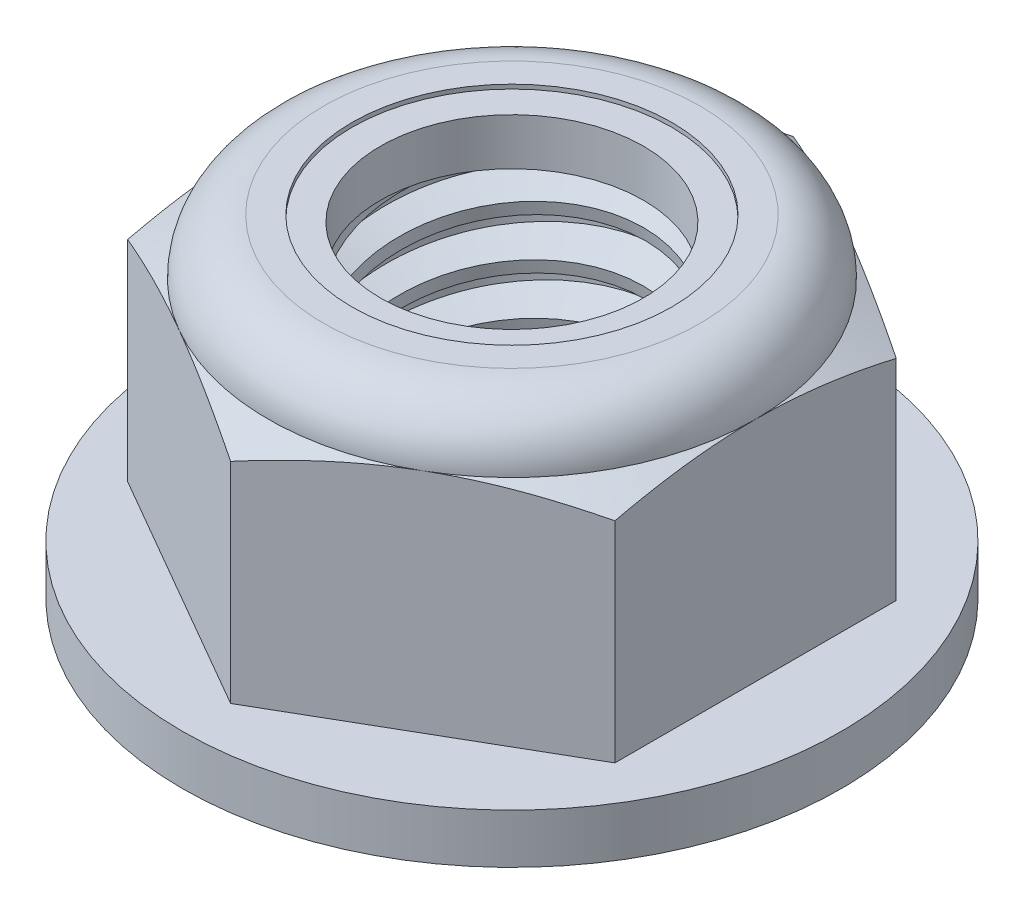
SolidWorks part; units mm, degrees
material "Alloy Steel"
ref_plane "Front" through (0, 0, 0) normal (0, 0, 1) x (1, 0, 0)
ref_plane "Top" through (0, 0, 0) normal (0, 1, 0) x (1, 0, 0)
ref_plane "Right" through (0, 0, 0) normal (1, 0, 0) x (0, 0, -1)
sketch "Sketch1" plane through (0, 0, 0) normal (0, 1, 0) x (1, 0, 0)
  line L1 (0, 10.082) -> (-8.7312, 5.041)
  line L2 (-8.7312, 5.041) -> (-8.7312, -5.041)
  line L3 (-8.7312, -5.041) -> (0, -10.082)
  line L4 (0, -10.082) -> (8.7312, -5.041)
  line L5 (8.7312, -5.041) -> (8.7312, 5.041)
  line L6 (8.7312, 5.041) -> (0, 10.082)
  circle A0 centre (0, 0) radius 8.7312 construction
  dimension "Hex Flats" = 17.4625
extrude "Extrude1" add sketch "Sketch1" along normal blind 11.9062
sketch "Sketch8" plane through (0, 0, 0) normal (1, 0, 0) x (0, 0, -1)
  line L0 (0, 0) -> (11.811, 0)
  line L1 (11.811, 0) -> (11.811, 1.778)
  line L2 (11.811, 1.778) -> (0, 1.778)
  line L3 (0, 1.778) -> (0, 0)
  line L4 (0, 0) -> (0, -1.778) construction
  dimension "Flange Height" = 1.778
  dimension "Flange Dia" = 23.622
revolve "Revolve3" add sketch "Sketch8" angle 360 about L4
sketch "Sketch2" plane through (0, 0, 0) normal (1, 0, 0) x (0, 0, -1)
  line L0 (-5.5563, 0) -> (-5.5563, 11.9062) construction
  line L1 (0, 0) -> (5.5563, 0)
  line L2 (0, 0) -> (0, 11.9062)
  line L3 (0, 11.9062) -> (5.5563, 11.9062)
  line L4 (5.5563, 0) -> (5.5563, 11.9062)
  line L5 (-5.041, 11.9062) -> (5.041, 11.9062) construction
  line L7 (0, -5.5563) -> (0, 0) construction
  dimension "Thread Dia" = 11.1125
revolve "Revolve1" add sketch "Sketch2" angle 360 about L7
sketch "Sketch3" plane through (0, 0, 0) normal (1, 0, 0) x (0, 0, -1)
  line L0 (5.5562, 11.9062) -> (-5.5563, 11.9062) construction
  line L1 (-5.5563, 11.9062) -> (-5.5563, 10.092) construction
  line L2 (-5.5563, 10.092) -> (5.5562, 11.9062) construction
  line L3 (5.5562, 11.9062) -> (5.5928, 11.6824) construction
  line L4 (5.5928, 11.6824) -> (5.8486, 10.1157)
  line L5 (5.8486, 10.1157) -> (4.7881, 10.517)
  line L6 (4.7881, 10.517) -> (4.715, 10.9646)
  line L7 (4.715, 10.9646) -> (5.5928, 11.6824)
  line L8 (4.7515, 10.7408) -> (5.7207, 10.899) construction
  line L9 (5.5562, 11.9062) -> (5.5563, 10.8722) construction
  line L10 (5.5563, 10.8722) -> (-5.5563, 9.0579) construction
  line L11 (-5.5563, 9.0579) -> (-5.5563, 10.092) construction
  line L12 (-0.3169, 11.9062) -> (0.3169, 8.0239) construction
  line L13 (-5.5563, 0) -> (-5.5563, 11.9062) construction
  line L14 (0, 11.9062) -> (5.5563, 11.9062) construction
  line L15 (5.5563, 0) -> (5.5563, 11.9062) construction
  point P13 (0, 9.9651)
  dimension "D1" = 0.2268
  dimension "D2" = 0.4536
  dimension "Thread Pitch" = 1.8143
  dimension "D4" = 60
  dimension "D5" = 1.8143
revolve "Cut-Revolve1" cut sketch "Sketch3" angle 360 about L12
pattern_linear "LPattern1" count 7 spacing 1.8143 along (0, 1, 0) count 2 spacing 1.8143 along (0, 1, 0) of "Cut-Revolve1"
sketch "Sketch4" plane through (0, 0, 0) normal (1, 0, 0) x (0, 0, -1)
  line L0 (0, 11.9062) -> (5.5563, 11.9062)
  line L1 (5.5563, 11.9062) -> (4.715, 11.514)
  line L2 (4.715, 11.514) -> (4.715, 0.3923)
  line L3 (4.715, 0.3923) -> (5.5563, 0)
  line L4 (5.5563, 0) -> (0, 0)
  line L5 (0, 0) -> (0, 11.9062)
  line L6 (5.5563, 0) -> (5.5563, 11.9062) construction
  line L7 (0, 11.9062) -> (5.5563, 11.9062) construction
  line L8 (0, 0) -> (5.5563, 0) construction
  line L9 (0, 0) -> (0, 11.9062) construction
  line L10 (0, 11.9062) -> (0, 12.8345) construction
  dimension "D1" = 25
revolve "Cut-Revolve2" cut sketch "Sketch4" angle 360 about L10
combine bodies "Combine1" operation type subtract main body 112 bodies to subtract 111
sketch "Sketch5" plane through (0, 0, 0) normal (1, 0, 0) x (0, 0, -1)
  line L0 (11.811, 1.778) -> (0, 1.778) construction
  line L1 (0, 0) -> (11.811, 0) construction
  line L2 (10.082, 1.778) -> (10.082, 9.292)
  line L3 (10.082, 9.292) -> (8.7312, 9.9219)
  line L4 (6.7469, 11.9062) -> (6.7469, 13.1762)
  line L5 (6.7469, 13.1762) -> (11.352, 13.1762)
  line L6 (11.352, 13.1762) -> (11.352, 1.778)
  line L9 (8.7312, 9.9219) -> (8.7312, 0) construction
  line L13 (10.082, 1.778) -> (11.352, 1.778)
  line L15 (0, 0) -> (0, 13.1762) construction
  line L20 (0, 13.1762) -> (6.7469, 13.1762) construction
  line L22 (0, 11.9062) -> (5.5563, 11.9062) construction
  arc A0 (8.7312, 9.9219) -> (6.7469, 11.9062) centre (6.7469, 9.9219) ccw
  dimension "D4" = 1.9844
  dimension "D1" = 1.27
  dimension "D2" = 115
  dimension "D3" = 11.9062
revolve "Cut-Revolve3" cut sketch "Sketch5" angle 360 about L15
sketch "Sketch6" plane through (0, 0, 0) normal (1, 0, 0) x (0, 0, -1)
  line L0 (0, 9.9219) -> (8.5788, 9.9219)
  line L1 (6.7469, 11.7538) -> (5.7309, 11.7538)
  line L2 (0, 13.1762) -> (0, 9.9219)
  line L3 (5.7309, 13.1762) -> (0, 13.1762)
  line L4 (0, 13.1762) -> (6.7469, 13.1762) construction
  line L5 (0, 0) -> (0, 13.1762) construction
  line L6 (0, 13.1762) -> (0, 44.323) construction
  line L7 (5.7309, 11.7538) -> (5.7309, 13.1762)
  line L8 (6.7469, 11.9062) -> (6.7469, 11.7538) construction
  line L9 (5.7309, 11.7538) -> (4.715, 11.7538) construction
  line L10 (4.715, 11.7538) -> (4.715, 11.514) construction
  arc A0 (8.5788, 9.9219) -> (6.7469, 11.7538) centre (6.7469, 9.9219) ccw
  arc A1 (8.7312, 9.9219) -> (6.7469, 11.9062) centre (6.7469, 9.9219) ccw construction
  dimension "D1" = 0.1524
revolve "Cut-Revolve4" cut sketch "Sketch6" angle 360 about L6
sketch "Sketch7" plane through (0, 0, 0) normal (1, 0, 0) x (0, 0, -1)
  line L0 (4.715, 9.9981) -> (8.501, 9.9981)
  line L1 (6.7469, 11.6776) -> (4.715, 11.6776)
  line L2 (4.715, 11.6776) -> (4.715, 9.9981)
  line L3 (4.715, 9.9981) -> (0, 9.9981) construction
  line L4 (0, 9.9981) -> (0, 11.6776) construction
  line L5 (0, 11.6776) -> (4.715, 11.6776) construction
  line L6 (4.715, 9.9981) -> (4.715, 9.9219) construction
  line L7 (0, 9.9219) -> (8.5788, 9.9219) construction
  line L8 (6.7469, 11.6776) -> (6.7469, 11.7538) construction
  arc A0 (8.501, 9.9981) -> (6.7469, 11.6776) centre (6.7469, 9.9219) ccw
  arc A2 (8.5788, 9.9219) -> (6.7469, 11.7538) centre (6.7469, 9.9219) ccw construction
  dimension "D1" = 0.0762
revolve "Revolve2" add sketch "Sketch7" angle 360 about L4
equation "\"D1@Sketch3\"=\"Thread Pitch@Sketch3\"/8"
equation "\"D2@Sketch3\"=\"Thread Pitch@Sketch3\"/4"
equation "\"D5@Sketch3\"=\"Thread Pitch@Sketch3\""
equation "\"D4@LPattern1\"=\"Thread Pitch@Sketch3\""
equation "\"D3@LPattern1\"=\"Thread Pitch@Sketch3\""
equation "\"D1@LPattern1\"=\"Height@Extrude1\"/\"Thread Pitch@Sketch3\""
equation "\"D4@Sketch5\"=\"Height@Extrude1\"/6"
